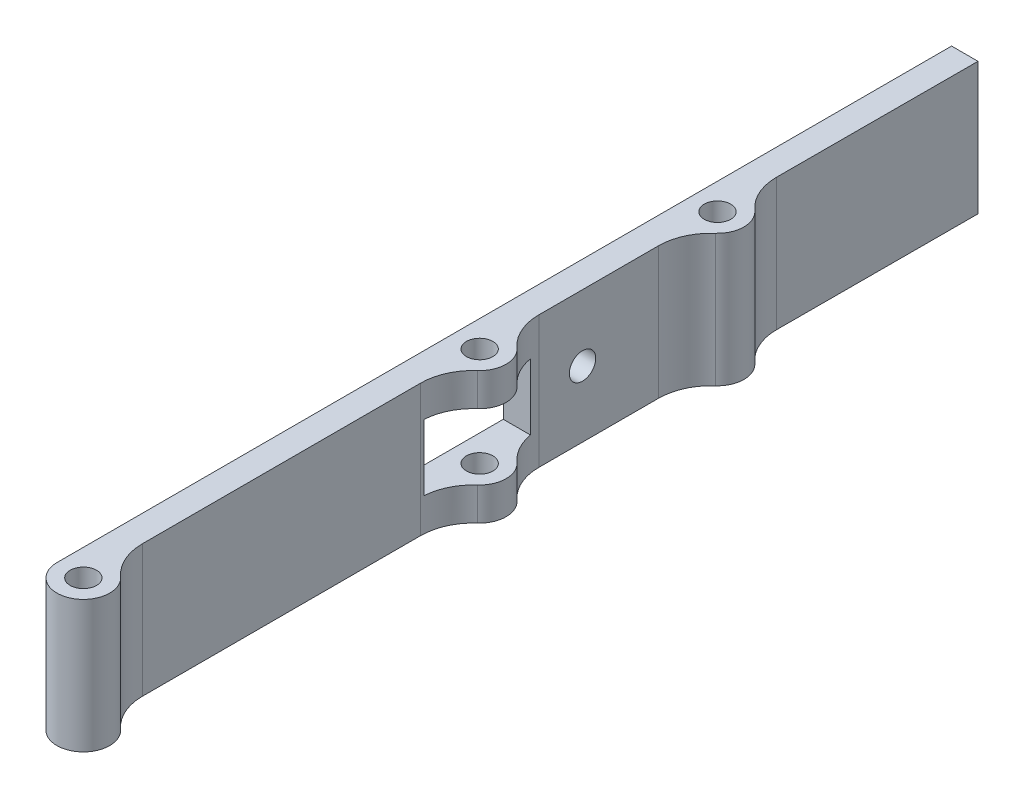
SolidWorks part; units mm, degrees
material "6061 Alloy"
ref_plane "Front Plane" through (0, 0, 0) normal (0, 0, 1) x (1, 0, 0)
ref_plane "Top Plane" through (0, 0, 0) normal (0, 1, 0) x (1, 0, 0)
ref_plane "Right Plane" through (0, 0, 0) normal (1, 0, 0) x (0, 0, -1)
sketch "Sketch2" plane through (0, 0, 0) normal (0, 1, 0) x (1, 0, 0)
  line L0 (0.0302, 33.8476) -> (0.0302, -135.4524)
  line L1 (0.0302, -135.4524) -> (5.0302, -135.4524) construction
  line L2 (0.0302, 33.8476) -> (5.0302, 33.8476)
  line L7 (5.0302, -24.2721) -> (5.0302, -49.2721) construction
  line L10 (5.0302, -26.6328) -> (5.0302, -49.2721)
  line L11 (5.0302, -71.6328) -> (5.0302, -135.4524) construction
  line L12 (5.0302, -71.6328) -> (5.0302, -124.2721)
  line L14 (5.0302, 33.8476) -> (4.9612, -4.1925)
  arc A0 (0.0302, -135.4524) -> (8.3636, -131.7257) centre (5.0302, -135.4524) ccw
  arc A1 (8.3636, -19.1792) -> (4.9498, -10.4531) centre (5.0302, -15.4524) ccw construction
  circle A2 centre (5.0302, -15.4524) radius 2.5
  circle A3 centre (5.0302, -135.4524) radius 2.5
  arc A5 (5.0302, -124.2721) -> (8.3636, -131.7257) centre (15.0302, -124.2721) ccw
  arc A6 (5.0302, -26.6328) -> (8.3636, -19.1792) centre (15.0302, -26.6328) cw
  arc A13 (8.3636, -64.1792) -> (8.3636, -56.7257) centre (5.0302, -60.4524) ccw
  circle A14 centre (5.0302, -60.4524) radius 2.5
  arc A15 (8.3636, -64.1792) -> (5.0302, -71.6328) centre (15.0302, -71.6328) ccw
  arc A16 (8.3636, -56.7257) -> (5.0302, -49.2721) centre (15.0302, -49.2721) cw
  arc A17 (8.3405, -11.7052) -> (8.3636, -19.1792) centre (5.0302, -15.4524) cw
  arc A18 (8.3405, -11.7052) -> (4.9612, -4.1925) centre (14.9611, -4.2107) cw
  point P13 (5.0302, -130.4524)
  dimension "D1" = 169.3
  dimension "D2" = 10
  dimension "D3" = 5
  dimension "D4" = 10
  dimension "D5" = 10
  dimension "D6" = 5
  dimension "D9" = 45
  dimension "D10" = 5
  dimension "D8" = 10
  dimension "D7" = 120
extrude "Boss-Extrude1" add sketch "Sketch2" along normal blind 25
sketch "Sketch3" plane through (0, 0, -33.8476) normal (0, 0, -1) x (-1, 0, 0)
  line L0 (-2.5, 25) -> (-2.5, 15) construction
  line L1 (-2.5, 15) -> (-2.5, 5) construction
  circle A2 centre (-2.5, 15) radius 1
  circle A3 centre (-2.5, 5) radius 1
  dimension "D1" = 10
  dimension "D2" = 10
extrude "Cut-Extrude1" cut sketch "Sketch3" against normal blind 25
sketch "Sketch6" plane through (0.0302, 0, 0) normal (-1, 0, 0) x (0, 0, 1)
  line L1 (-34.0109, 0) -> (-34.0109, 25) construction
  line L8 (50.9891, 6.25) -> (50.9891, 18.75)
  line L11 (70.9891, 6.25) -> (70.9891, 18.75)
  line L13 (50.9891, 18.75) -> (70.9891, 18.75)
  line L14 (70.9891, 6.25) -> (50.9891, 6.25)
  line L15 (-33.8476, 25) -> (135.4524, 25) construction
  line L16 (-33.8476, 0) -> (135.4524, 0) construction
  circle A0 centre (40.9891, 12.5) radius 2.5
  dimension "D2" = 6.25
  dimension "D7" = 10
  dimension "D1" = 25
  dimension "D3" = 12.5
  dimension "D4" = 20
  dimension "D5" = 6.25
  dimension "D6" = 85
extrude "Cut-Extrude2" cut sketch "Sketch6" against normal through all
